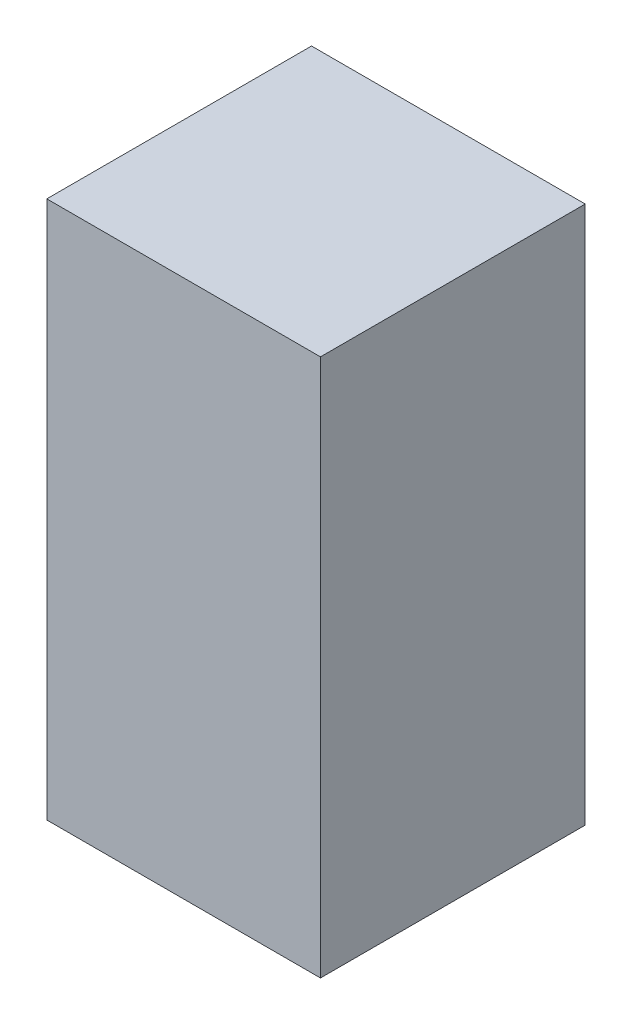
SolidWorks part; units mm, degrees
ref_plane "Front Plane" through (0, 0, 0) normal (0, 0, 1) x (1, 0, 0)
ref_plane "Top Plane" through (0, 0, 0) normal (0, 1, 0) x (1, 0, 0)
ref_plane "Right Plane" through (0, 0, 0) normal (1, 0, 0) x (0, 0, -1)
sketch "Sketch1" plane through (0, 0, 0) normal (0, 0, 1) x (1, 0, 0)
  line L0 (-9.017, 18.7198) -> (1.3208, 18.7198)
  line L1 (1.3208, 18.7198) -> (1.3208, -1.6002)
  line L2 (1.3208, -1.6002) -> (-9.017, -1.6002)
  line L3 (-9.017, -1.6002) -> (-9.017, 18.7198)
extrude "Component_Outline" add sketch "Sketch1" along normal blind 10 separate body
sketch3d "3DSketch1"
  line L0 (0, 0, 0) -> (1, 0, 0)
  line L1 (0, 0, 0) -> (0, 1, 0)
  line L2 (0, 0, 0) -> (0, 0, 1)
  point P0 (0, 0, 0)
